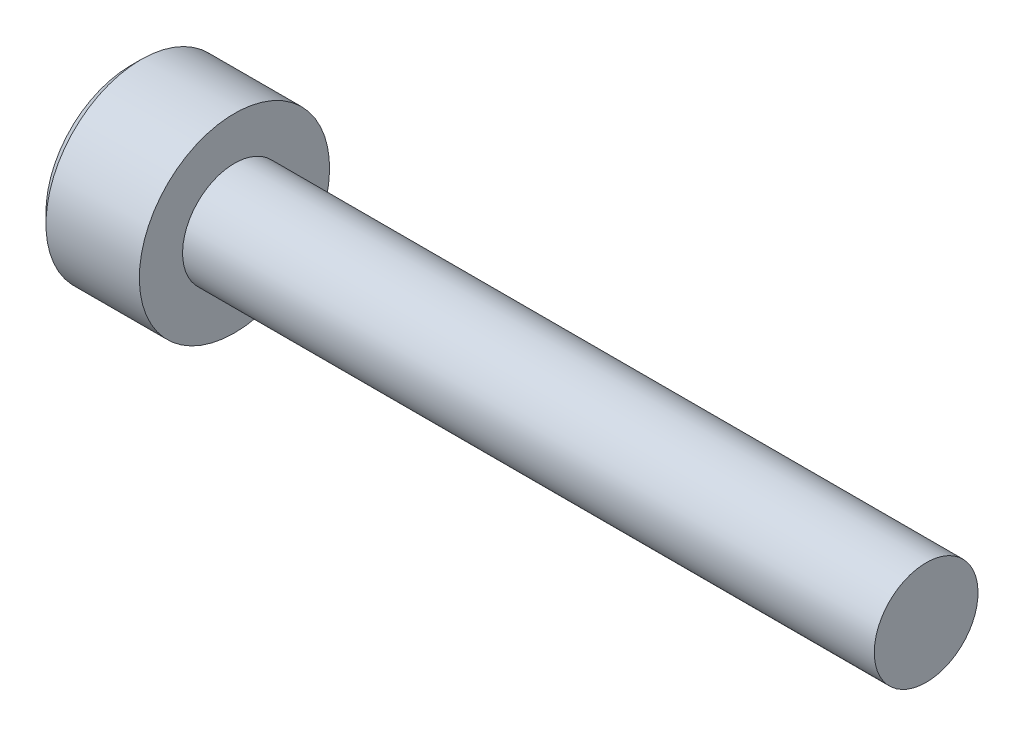
SolidWorks part; units mm, degrees
material "SCM435"
ref_plane "Front Plane" through (0, 0, 0) normal (0, 0, 1) x (1, 0, 0)
ref_plane "Top Plane" through (0, 0, 0) normal (0, 1, 0) x (1, 0, 0)
ref_plane "Right Plane" through (0, 0, 0) normal (1, 0, 0) x (0, 0, -1)
sketch "Sketch1" plane through (0, 0, 0) normal (0, 0, 1) x (1, 0, 0)
  line L0 (-3, 0) -> (20, 0) construction
  line L1 (0, 1.5) -> (20, 1.5)
  line L3 (-3, 0) -> (20, 0)
  line L4 (20, 1.5) -> (20, 0)
  line L6 (0, 1.5) -> (0, 2.75)
  line L7 (0, 2.75) -> (-3, 2.75)
  line L8 (-3, 0) -> (-3, 2.75)
  dimension "L" = 20
  dimension "M" = 3
  dimension "E" = 3
  dimension "A" = 5.5
revolve "Revolve1" add sketch "Sketch1" about L0
cosmetic thread "Thread1" parameters "L_s"=20, "ATD"=2.459
chamfer "Chamfer1" distance 0.3 1 edges at (-3, -2.75, 0)
sketch "Sketch2" plane through (0, 0, 0) normal (0, 0, 1) x (1, 0, 0)
  line L0 (-0.9489, 0) -> (-1.7, 1.25)
  line L1 (-3, 0) -> (20, 0) construction
  line L2 (-1.7, 1.25) -> (-3, 1.25)
  line L3 (-3, 1.25) -> (-3, 0)
  line L4 (-3, 0) -> (-0.9489, 0) construction
  line L5 (-0.9489, 0) -> (-3, 0)
  dimension "FIX_2" = 59
  dimension "MSM_1" = 1.3
revolve "Cut-Revolve1" cut sketch "Sketch2" about L4
sketch "Sketch3" plane through (-3, 0, 0) normal (-1, 0, 0) x (0, 0, 1)
  line L0 (0, -3.025) -> (0, 3.025) construction
  line L1 (1.25, 0.7217) -> (0, 1.4434)
  line L2 (0, 1.4434) -> (-1.25, 0.7217)
  line L3 (-1.25, 0.7217) -> (-1.25, -0.7217)
  line L4 (-1.25, -0.7217) -> (0, -1.4434)
  line L5 (0, -1.4434) -> (1.25, -0.7217)
  line L6 (1.25, -0.7217) -> (1.25, 0.7217)
  circle A0 centre (0, 0) radius 1.25 construction
extrude "Cut-Extrude1" cut sketch "Sketch3" against normal blind 1.3
